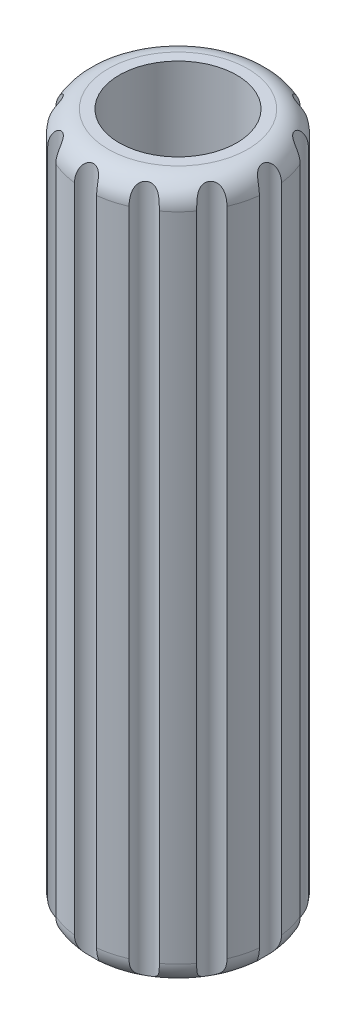
SolidWorks part; units mm, degrees
material "Natural Rubber"
ref_plane "Front Plane" through (0, 0, 0) normal (0, 0, 1) x (1, 0, 0)
ref_plane "Top Plane" through (0, 0, 0) normal (0, 1, 0) x (1, 0, 0)
ref_plane "Right Plane" through (0, 0, 0) normal (1, 0, 0) x (0, 0, -1)
sketch "Sketch1" plane through (0, 0, 0) normal (0, 1, 0) x (1, 0, 0)
  circle A0 centre (0, 0) radius 16
  dimension "D1" = 32
extrude "Boss-Extrude1" add sketch "Sketch1" along normal blind 120
fillet "Fillet1" radius 4 2 edges at (0, 120, 16) (0, 0, 16)
sketch "Sketch2" plane through (0, 120, 0) normal (0, 1, 0) x (1, 0, 0)
  circle A0 centre (0, 0) radius 10.1
  dimension "D1" = 20.2
extrude "Cut-Extrude1" cut sketch "Sketch2" against normal blind 116 and the other way through all
sketch "Sketch3" plane through (0, 0, 0) normal (0, 1, 0) x (1, 0, 0)
  line L0 (0, 16.4862) -> (0, -16.4018) construction
  circle A0 centre (0, 16.5) radius 2
  circle A22 centre (8.25, 14.2894) radius 2
  circle A23 centre (14.2894, 8.25) radius 2
  circle A24 centre (16.5, 0) radius 2
  circle A25 centre (14.2894, -8.25) radius 2
  circle A26 centre (8.25, -14.2894) radius 2
  circle A27 centre (0, -16.5) radius 2
  circle A28 centre (-8.25, -14.2894) radius 2
  circle A29 centre (-14.2894, -8.25) radius 2
  circle A30 centre (-16.5, 0) radius 2
  circle A31 centre (-14.2894, 8.25) radius 2
  circle A32 centre (-8.25, 14.2894) radius 2
  dimension "D1" = 4
  dimension "D2" = 16.5
extrude "Cut-Extrude2" cut sketch "Sketch3" along normal through all
